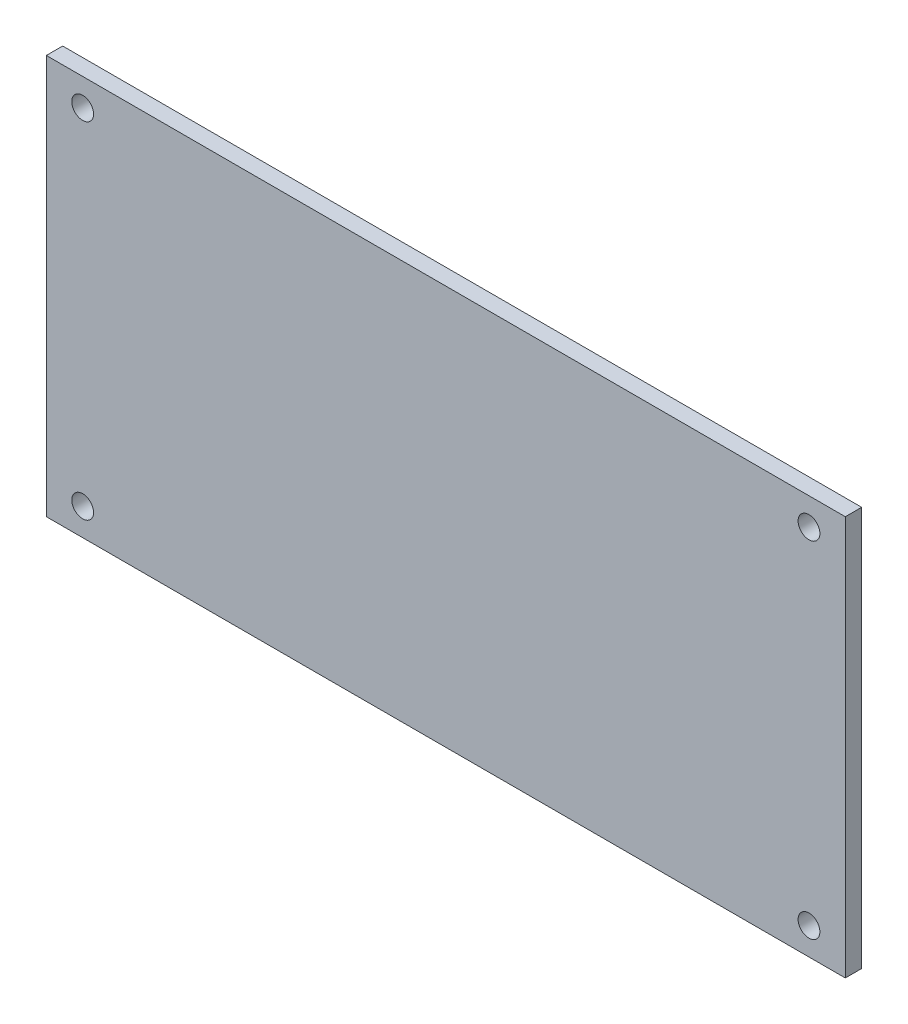
SolidWorks part; units mm, degrees
ref_plane "Спереди" through (0, 0, 0) normal (0, 0, 1) x (1, 0, 0)
ref_plane "Сверху" through (0, 0, 0) normal (0, 1, 0) x (1, 0, 0)
ref_plane "Справа" through (0, 0, 0) normal (1, 0, 0) x (0, 0, -1)
sketch "Эскиз1" plane through (0, 0, 0) normal (0, 0, 1) x (1, 0, 0)
  line L0 (60.5, 0) -> (-60.5, 0) construction
  line L1 (-55, -27.5) -> (55, -27.5)
  line L2 (-55, -27.5) -> (-55, 27.5)
  line L3 (-55, 27.5) -> (55, 27.5)
  line L4 (55, -27.5) -> (55, 27.5)
  line L5 (-55, -27.5) -> (55, 27.5) construction
  line L6 (-55, 27.5) -> (55, -27.5) construction
  line L7 (0, -28.6) -> (0, 28.6) construction
  circle A0 centre (-50, 23.75) radius 1.5
  circle A1 centre (-50, -23.75) radius 1.5
  circle A2 centre (50, -23.75) radius 1.5
  circle A3 centre (50, 23.75) radius 1.5
  point P0 (0, 0)
  dimension "D4" = 3
  dimension "D1" = 110
  dimension "D2" = 55
  dimension "D3" = 50
  dimension "D5" = 47.5
extrude "Бобышка-Вытянуть1" add sketch "Эскиз1" along normal blind 2.25 contours L1 L4 L3 L2 A1 A0 A2 A3
